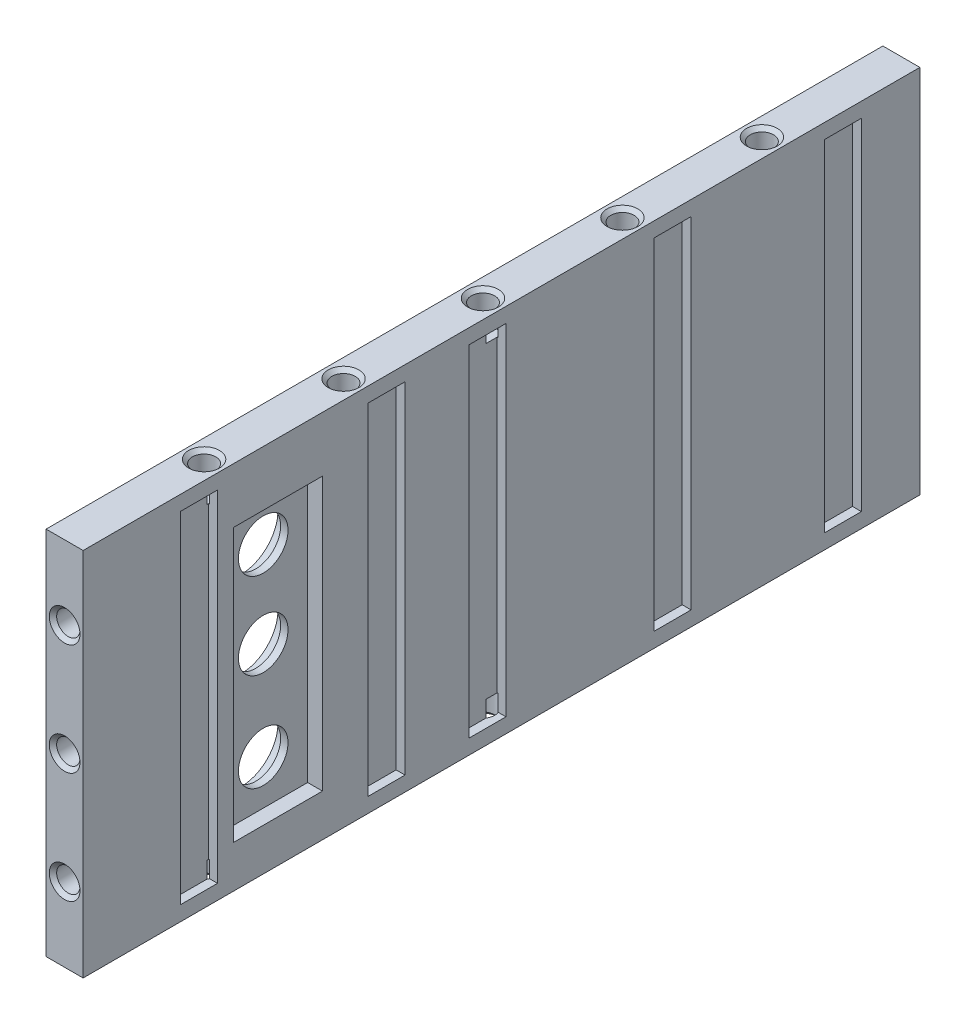
SolidWorks part; units mm, degrees
ref_plane "Спереди" through (0, 0, 0) normal (0, 0, 1) x (1, 0, 0)
ref_plane "Сверху" through (0, 0, 0) normal (0, 1, 0) x (1, 0, 0)
ref_plane "Справа" through (0, 0, 0) normal (1, 0, 0) x (0, 0, -1)
sketch "Эскиз1" plane through (0, 0, 0) normal (1, 0, 0) x (0, 0, -1)
  line L1 (-113, 25) -> (0, 25)
  line L2 (-113, 25) -> (-113, -25)
  line L3 (-113, -25) -> (0, -25)
  line L4 (0, 25) -> (0, -25)
  point P4 (0, 0)
  dimension "D1" = 113
  dimension "D2" = 50
extrude "Бобышка-Вытянуть1" add sketch "Эскиз1" along normal blind 5
ref_plane "Плоскость1" through (0, 0, 0) normal (0, -1, 0) x (-1, 0, 0)
sketch "Эскиз2" plane through (0, -25, 0) normal (0, -1, 0) x (1, 0, 0)
  line L0 (2.5, 113) -> (2.5, 94.1667) construction
  line L1 (5, 113) -> (0, 113) construction
  line L2 (2.5, 94.1667) -> (2.5, 75.3333) construction
  line L3 (2.5, 75.3333) -> (2.5, 56.5) construction
  line L4 (2.5, 56.5) -> (2.5, 37.6667) construction
  line L5 (2.5, 37.6667) -> (2.5, 18.8333) construction
  line L6 (2.5, 18.8333) -> (2.5, 0) construction
  line L7 (5, 0) -> (0, 0) construction
  line L8 (5, 113) -> (5, 0) construction
  circle A0 centre (2.5, 94.1667) radius 1.575
  circle A1 centre (2.5, 75.3333) radius 1.575
  circle A2 centre (2.5, 56.5) radius 1.575
  circle A3 centre (2.5, 37.6667) radius 1.575
  circle A4 centre (2.5, 18.8333) radius 1.575
  dimension "D3" = 3.15
  dimension "D2" = 2.5
  dimension "D1" = 5
extrude "Крепежные отверстия верхней и нижней крышки" cut sketch "Эскиз2" against normal blind 4.2
mirror "Зеркальное отражение1" about plane through (0, 0, 0) normal (0, -1, 0) of "Крепежные отверстия верхней и нижней крышки"
ref_plane "Плоскость2" through (0, 0, 56.5) normal (0, 0, -1) x (-1, 0, 0)
sketch "Эскиз3" plane through (0, 0, 113) normal (0, 0, 1) x (1, 0, 0)
  line L0 (-2.9169, 30) -> (11.1229, 30) construction
  line L1 (-5.1832, -30) -> (8.8566, -30) construction
  line L2 (5, 25) -> (5, 30) construction
  line L3 (5, -25) -> (5, -30) construction
  line L4 (2.5, 30) -> (2.5, 15) construction
  line L5 (2.5, 15) -> (2.5, 0) construction
  line L6 (2.5, 0) -> (2.5, -15) construction
  line L7 (2.5, -15) -> (2.5, -30) construction
  line L8 (5, 25) -> (5, -25) construction
  circle A0 centre (2.5, 15) radius 1.575
  circle A1 centre (2.5, 0) radius 1.575
  circle A2 centre (2.5, -15) radius 1.575
  dimension "D4" = 3.15
  dimension "D1" = 5
  dimension "D3" = 2.5
  dimension "D2" = 3
extrude "Крепежные отверстия лицевой и задней стороны" cut sketch "Эскиз3" against normal blind 4.2
mirror "Зеркальное отражение2" about plane through (0, 0, 56.5) normal (0, 0, -1) of "Крепежные отверстия лицевой и задней стороны"
sketch "Эскиз4" plane through (5, 0, 0) normal (1, 0, 0) x (0, 0, -1)
  line L0 (-5.9, 41.7127) -> (-5.9, -32.2038) construction
  line L1 (0, -25) -> (0, 25) construction
  line L2 (-7.9, 23) -> (-7.9, 25) construction
  line L3 (-12.9, 23) -> (-7.9, 23)
  line L4 (-12.9, 23) -> (-12.9, -23)
  line L5 (-12.9, -23) -> (-7.9, -23)
  line L6 (-7.9, 23) -> (-7.9, -23)
  line L7 (0, 25) -> (-113, 25) construction
  line L8 (-7.9, -23) -> (-7.9, -25) construction
  line L9 (-113, -25) -> (0, -25) construction
  line L10 (-21.9, 29.9409) -> (-21.9, -27.9732) construction
  line L11 (-45.9, 27.9425) -> (-45.9, -29.5532) construction
  line L12 (-35.9, 23) -> (-35.9, -23)
  line L13 (-30.9, -23) -> (-35.9, -23)
  line L14 (-30.9, 23) -> (-30.9, -23)
  line L15 (-30.9, 23) -> (-35.9, 23)
  line L16 (-60.9, 23) -> (-55.9, 23)
  line L17 (-60.9, 23) -> (-60.9, -23)
  line L18 (-60.9, -23) -> (-55.9, -23)
  line L19 (-55.9, 23) -> (-55.9, -23)
  line L20 (-65.215, 29.9409) -> (-65.215, -28.7246) construction
  line L21 (-74.53, 23) -> (-74.53, -23)
  line L22 (-69.53, -23) -> (-74.53, -23)
  line L23 (-69.53, 23) -> (-69.53, -23)
  line L24 (-69.53, 23) -> (-74.53, 23)
  line L25 (-84.69, 29.9409) -> (-84.69, -31.641) construction
  line L26 (-99.85, 23) -> (-94.85, 23)
  line L27 (-99.85, 23) -> (-99.85, -23)
  line L28 (-99.85, -23) -> (-94.85, -23)
  line L29 (-94.85, 23) -> (-94.85, -23)
  dimension "D1" = 5.9
  dimension "D2" = 5
  dimension "D3" = 2
  dimension "D4" = 46
  dimension "D5" = 23
  dimension "D6" = 25
  dimension "D7" = 13.63
  dimension "D8" = 25.32
extrude "Выбор под контакты" cut sketch "Эскиз4" against normal blind 1.2
sketch "Эскиз5" plane through (5, 0, 0) normal (1, 0, 0) x (0, 0, -1)
  line L0 (-86.68, 31.4583) -> (-86.68, -34.9653) construction
  line L1 (0, 25) -> (-113, 25) construction
  line L2 (-69.53, -23) -> (-69.53, 23) construction
  circle A0 centre (-86.68, 11.54) radius 3.35
  circle A1 centre (-86.68, -0.09) radius 3.35
  circle A2 centre (-86.68, -13.3) radius 3.35
  dimension "D1" = 6.7
  dimension "D2" = 13.46
  dimension "D3" = 11.63
  dimension "D4" = 13.21
  dimension "D5" = 17.15
extrude "SMA раземы" cut sketch "Эскиз5" against normal through all
sketch "Эскиз6" plane through (0, 0, 0) normal (-1, 0, 0) x (0, 0, 1)
  circle A0 centre (86.68, 11.54) radius 5
  circle A1 centre (86.68, -0.09) radius 5
  circle A2 centre (86.68, -13.3) radius 5
  dimension "D1" = 10
extrude "SMA раземы2" cut sketch "Эскиз6" against normal blind 2
sketch "Эскиз7" plane through (5, 0, 0) normal (1, 0, 0) x (0, 0, -1)
  line L1 (-80.68, 17.54) -> (-92.68, 17.54)
  line L2 (-80.68, 17.54) -> (-80.68, -19.3)
  line L3 (-80.68, -19.3) -> (-92.68, -19.3)
  line L4 (-92.68, 17.54) -> (-92.68, -19.3)
  circle A0 centre (-86.68, -13.3) radius 3.35 construction
  circle A1 centre (-86.68, 11.54) radius 3.35 construction
  dimension "D1" = 6
  dimension "D2" = 6
  dimension "D3" = 6
  dimension "D4" = 6
extrude "SMA раземы3" cut sketch "Эскиз7" against normal blind 2
chamfer "Фаска под запресовку" distance 0.5 angle 45 16 edges at (4.075, 15, 0) (4.075, 0, 0) (4.075, -15, 0) (2.5, -25, 17.2583) (2.5, -25, 36.0917) (2.5, -25, 54.925) (2.5, -25, 73.7583) (2.5, -25, 92.5917) (4.075, -15, 113) (4.075, 0, 113) (4.075, 15, 113) (2.5, 25, 92.5917) (2.5, 25, 73.7583) (2.5, 25, 54.925) (2.5, 25, 36.0917) (2.5, 25, 17.2583)
